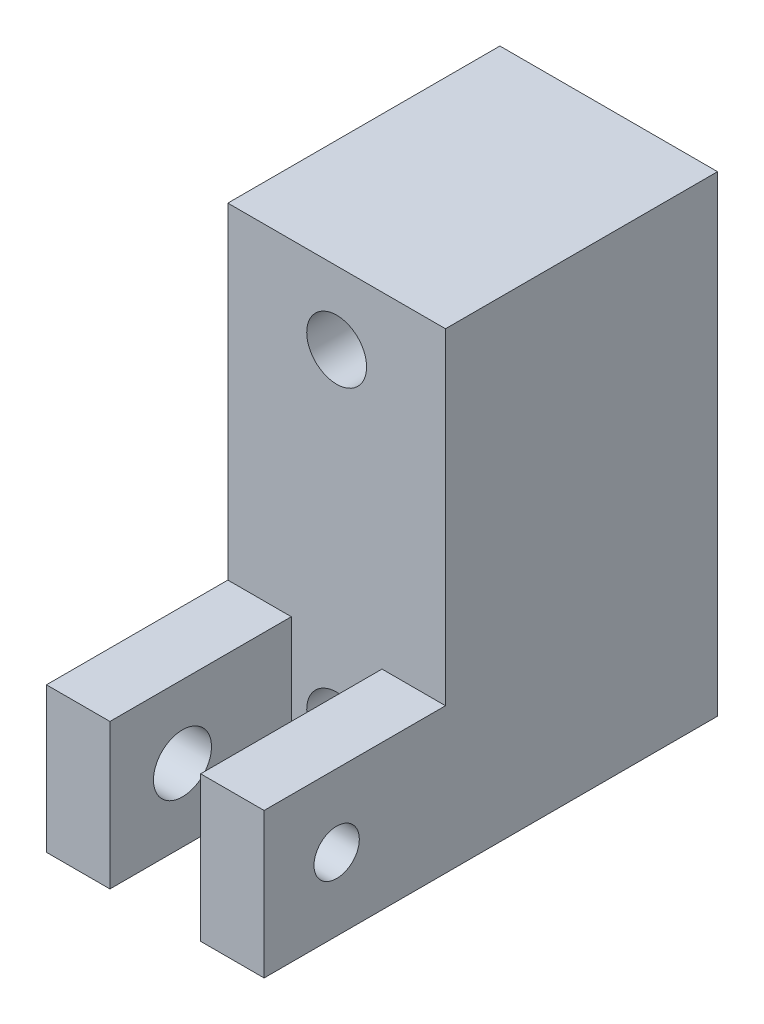
SolidWorks part; units mm, degrees
ref_plane "前视基准面" through (0, 0, 0) normal (0, 0, 1) x (1, 0, 0)
ref_plane "上视基准面" through (0, 0, 0) normal (0, 1, 0) x (1, 0, 0)
ref_plane "右视基准面" through (0, 0, 0) normal (1, 0, 0) x (0, 0, -1)
sketch "草图1" plane through (0, 0, 0) normal (1, 0, 0) x (0, 0, -1)
  line L1 (-7.5, -13) -> (7.5, -13)
  line L2 (-7.5, -5) -> (-7.5, 13)
  line L3 (-7.5, 13) -> (7.5, 13)
  line L4 (7.5, -13) -> (7.5, 13)
  line L5 (-7.5, -13) -> (7.5, 13) construction
  line L6 (-7.5, 13) -> (7.5, -13) construction
  line L7 (-7.5, -13) -> (-17.5, -13)
  line L9 (-7.5, -5) -> (-17.5, -5)
  line L10 (-17.5, -13) -> (-17.5, -5)
  point P0 (0, 0)
  dimension "D1" = 10
  dimension "D2" = 8
  dimension "D3" = 26
  dimension "D4" = 15
extrude "凸台-拉伸1" add sketch "草图1" along normal mid plane 12
sketch "草图2" plane through (0, -5, 0) normal (0, 1, 0) x (1, 0, 0)
  line L0 (6, -7.5) -> (-6, -7.5) construction
  line L1 (-2.5, -17.5) -> (2.5, -17.5)
  line L2 (-2.5, -17.5) -> (-2.5, -7.5)
  line L3 (-2.5, -7.5) -> (2.5, -7.5)
  line L4 (2.5, -17.5) -> (2.5, -7.5)
  line L5 (-2.5, -17.5) -> (2.5, -7.5) construction
  line L6 (-2.5, -7.5) -> (2.5, -17.5) construction
  line L7 (6, -17.5) -> (-6, -17.5) construction
  point P0 (0, -12.5)
  dimension "D1" = 5
extrude "切除-拉伸1" cut sketch "草图2" against normal up to next
hole_wizard "M3 螺纹孔1" positions "草图4" profile "草图3" tap size "M3" standard "GB"
sketch "草图4" plane through (6, 0, 0) normal (1, 0, 0) x (0, 0, -1)
  line L0 (-17.5, -5) -> (-17.5, -13) construction
  line L1 (-13.5, -9) -> (-17.5, -9) construction
  point P0 (-13.5, -9)
  dimension "D1" = 4
sketch "草图3" plane through (6, -9, 13.5) normal (0, 1, 0) x (0, 0, -1)
  line L0 (0, 0) -> (0, 3.5)
  line L1 (0, 3.5) -> (1.25, 3.5)
  line L2 (1.25, 3.5) -> (1.25, 0)
  line L5 (1.25, 0) -> (0, 0)
  line L11 (0, -6.35) -> (0, 107.95) construction
  dimension "通孔螺纹孔钻头直径" = 2.5
  dimension "通孔螺纹孔钻头深度" = 3.5
cosmetic thread "孔螺蚊线1" parameters "D2"=3
hole_wizard "M3 间隙孔1" positions "草图6" profile "草图5" hole size "M3" standard "GB"
sketch "草图6" plane through (-6, 0, 0) normal (-1, 0, 0) x (0, 0, 1)
  point P0 (13.5, -9)
sketch "草图5" plane through (-6, -9, 13.5) normal (0, 1, 0) x (0, 0, 1)
  line L0 (0, 0) -> (0, 3.5)
  line L1 (0, 3.5) -> (1.6, 3.5)
  line L2 (1.6, 3.5) -> (1.6, 0)
  line L5 (1.6, 0) -> (0, 0)
  line L11 (0, -6.35) -> (0, 107.95) construction
  dimension "通孔孔直径" = 3.2
  dimension "通孔孔深度" = 3.5
hole_wizard "M4 螺纹孔2" positions "草图8" profile "草图7" tap size "M4" standard "GB" end condition up to next
sketch "草图8" plane through (0, 0, -7.5) normal (0, 0, -1) x (-1, 0, 0)
  line L0 (-6, -13) -> (6, -13) construction
  point P0 (0, -9)
  dimension "D1" = 4
sketch "草图7" plane through (0, -9, -7.5) normal (1, 0, 0) x (0, 1, 0)
  line L0 (0, 0) -> (0, 15)
  line L1 (0, 15) -> (1.65, 15)
  line L2 (1.65, 15) -> (1.65, 0)
  line L5 (1.65, 0) -> (0, 0)
  line L11 (0, -6.35) -> (0, 107.95) construction
  dimension "螺纹线主直径" = 3.3
  dimension "通孔螺纹孔钻头深度" = 15
hole_wizard "M4 螺纹孔1" positions "草图10" profile "草图9" tap size "M4" standard "GB" end condition up to next
sketch "草图10" plane through (0, 0, -7.5) normal (0, 0, -1) x (-1, 0, 0)
  circle A0 centre (0, -9) radius 1.65 construction
  point P0 (0, 9)
  dimension "D1" = 18
sketch "草图9" plane through (0, 9, -7.5) normal (1, 0, 0) x (0, 1, 0)
  line L0 (0, 0) -> (0, 15)
  line L1 (0, 15) -> (1.65, 15)
  line L2 (1.65, 15) -> (1.65, 0)
  line L5 (1.65, 0) -> (0, 0)
  line L11 (0, -6.35) -> (0, 107.95) construction
  dimension "通孔螺纹孔钻头直径" = 3.3
  dimension "通孔螺纹孔钻头深度" = 15
cosmetic thread "孔螺蚊线2" parameters "D2"=4
